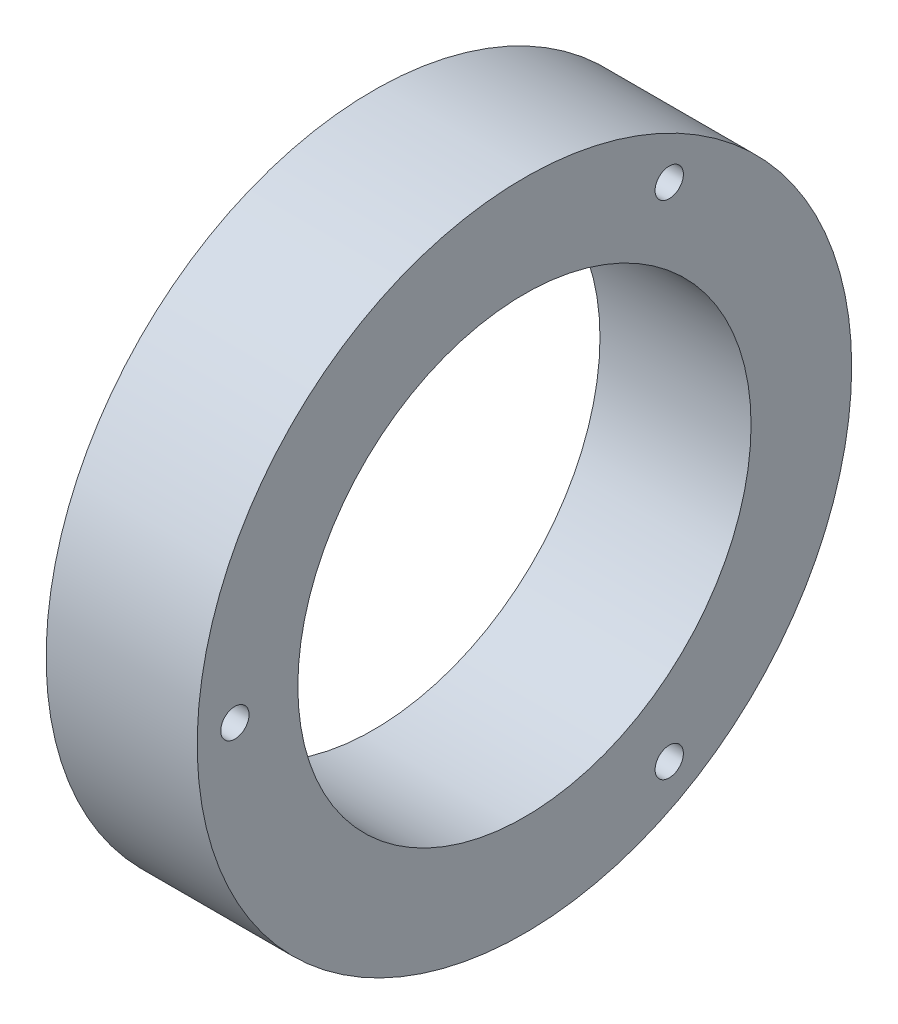
SolidWorks part; units mm, degrees
ref_plane "Front Plane" through (0, 0, 0) normal (1, 0, 0) x (0, 1, 0)
ref_plane "Top Plane" through (0, 0, 0) normal (0, 0, 1) x (0, 1, 0)
ref_plane "Right Plane" through (0, 0, 0) normal (0, 1, 0) x (-1, 0, 0)
sketch "Sketch1" plane through (0, 0, 0) normal (1, 0, 0) x (0, 1, 0)
  circle A0 centre (0, 0) radius 82.5246
extrude "Boss-Extrude1" add sketch "Sketch1" along normal blind 38.1
sketch "Sketch2" plane through (0, 0, 0) normal (1, 0, 0) x (0, 1, 0)
  circle A0 centre (0, 0) radius 57.15
extrude "Cut-Extrude1" cut sketch "Sketch2" along normal blind 38.1
sketch "Sketch3" plane through (0, 0, 0) normal (1, 0, 0) x (0, 1, 0)
  circle A0 centre (0, 73.025) radius 3.5687
  circle A1 centre (-63.2415, -36.5125) radius 3.5687
  circle A2 centre (63.2415, -36.5125) radius 3.5687
extrude "Cut-Extrude3" cut sketch "Sketch3" along normal through all
sketch "Sketch4" plane through (0, 0, 0) normal (1, 0, 0) x (0, 1, 0)
  circle A0 centre (0, 73.025) radius 5.5626
  circle A1 centre (-63.2415, -36.5125) radius 5.5626
  circle A2 centre (63.2415, -36.5125) radius 5.5626
extrude "Cut-Extrude4" cut sketch "Sketch4" along normal blind 9.652
